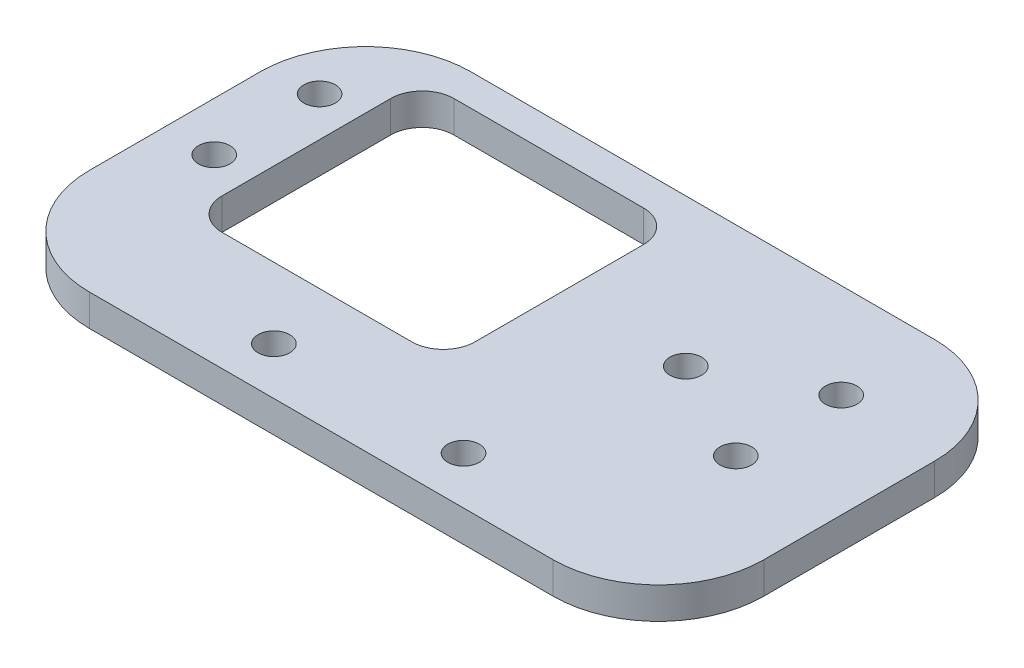
SolidWorks part; units mm, degrees
material "Thornel Mat VMA"
ref_plane "前视基准面" through (0, 0, 0) normal (0, 0, 1) x (1, 0, 0)
ref_plane "上视基准面" through (0, 0, 0) normal (0, 1, 0) x (1, 0, 0)
ref_plane "右视基准面" through (0, 0, 0) normal (1, 0, 0) x (0, 0, -1)
other "Configuration Table"
sketch "草图1" plane through (0, 0, 0) normal (0, 1, 0) x (1, 0, 0)
  line L0 (0, 0) -> (0, 16.2916) construction
  line L1 (-32, -18.1) -> (32, -18.1)
  line L2 (-32, -18.1) -> (-32, 18.1)
  line L3 (-32, 18.1) -> (32, 18.1)
  line L4 (32, -18.1) -> (32, 18.1)
  line L5 (-32, -18.1) -> (32, 18.1) construction
  line L6 (-32, 18.1) -> (32, -18.1) construction
  line L7 (0, 4.1) -> (47.3181, 4.1) construction
  line L8 (-2.61, 4.1) -> (-2.61, 28.4843) construction
  line L9 (-23.61, -6.9) -> (18.39, -6.9)
  line L10 (-23.61, -6.9) -> (-23.61, 15.1)
  line L11 (-23.61, 15.1) -> (18.39, 15.1)
  line L12 (18.39, -6.9) -> (18.39, 15.1)
  line L13 (-23.61, -6.9) -> (18.39, 15.1) construction
  line L14 (-23.61, 15.1) -> (18.39, -6.9) construction
  line L15 (-12.5, 4.1) -> (-12.5, 27.2071) construction
  line L16 (10, 4.1) -> (10, 32.7726) construction
  circle A2 centre (22.14, 9.1) radius 1.5
  circle A3 centre (22.14, -0.9) radius 1.5
  circle A4 centre (-27.36, -0.9) radius 1.5
  circle A5 centre (-27.36, 9.1) radius 1.5
  circle A6 centre (9, -13.6) radius 1.5
  circle A7 centre (-9, -13.6) radius 1.5
  point P0 (0, 0)
  point P14 (-2.61, 4.1)
  dimension "D3" = 3
  dimension "D4" = 18
  dimension "D5" = 4.5
  dimension "D11" = 3
  dimension "D12" = 10
  dimension "D13" = 49.5
  dimension "D1" = 64
  dimension "D2" = 36.2
  dimension "D6" = 42
  dimension "D7" = 22
  dimension "D8" = 9.89
  dimension "D9" = 12.5
  dimension "D10" = 14
  dimension "D14" = 10
extrude "凸台-拉伸1" add sketch "草图1" along normal blind 3
sketch "草图2" plane through (0, 3, 0) normal (0, 1, 0) x (1, 0, 0)
  line L0 (0.39, 15.1) -> (0.39, -6.9)
  line L3 (0.39, -6.9) -> (18.39, -6.9)
  line L4 (18.39, -6.9) -> (18.39, 15.1)
  line L5 (18.39, 15.1) -> (0.39, 15.1)
  dimension "D1" = 18
extrude "凸台-拉伸2" add sketch "草图2" against normal blind 3
sketch "草图3" plane through (0, 3, 0) normal (0, 1, 0) x (1, 0, 0)
  line L0 (0.39, 4.1) -> (22.14, 4.1) construction
  line L1 (0.39, 15.1) -> (0.39, -6.9) construction
  line L3 (22.14, 9.1) -> (22.14, -0.9) construction
  circle A0 centre (12.39, 4.1) radius 1.5
  dimension "D2" = 3
  dimension "D3" = 12
extrude "切除-拉伸1" cut sketch "草图3" against normal blind 3
fillet "圆角1" radius 10 4 edges at (-32, 1.5, -18.1) (32, 1.5, -18.1) (32, 1.5, 18.1) (-32, 1.5, 18.1)
fillet "圆角2" radius 3 4 edges at (0.39, 1.5, 6.9) (0.39, 1.5, -15.1) (-23.61, 1.5, -15.1) (-23.61, 1.5, 6.9)
